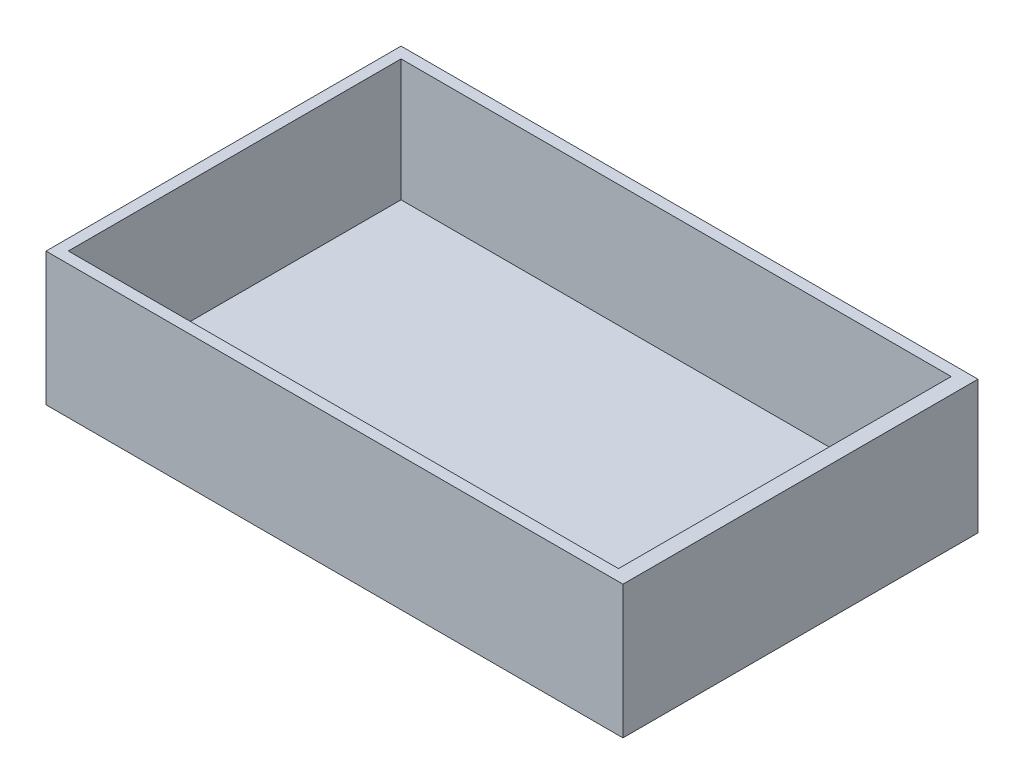
SolidWorks part; units mm, degrees
material "Teak"
ref_plane "Ebene vorne" through (0, 0, 0) normal (0, 0, 1) x (1, 0, 0)
ref_plane "Ebene oben" through (0, 0, 0) normal (0, 1, 0) x (1, 0, 0)
ref_plane "Ebene rechts" through (0, 0, 0) normal (1, 0, 0) x (0, 0, -1)
sketch "Skizze1" plane through (0, 0, 0) normal (0, 1, 0) x (1, 0, 0)
  line L1 (0, 0) -> (520, 0)
  line L2 (0, 0) -> (0, 320)
  line L3 (0, 320) -> (520, 320)
  line L4 (520, 0) -> (520, 320)
  dimension "D1" = 520
  dimension "D2" = 320
extrude "Aufsatz-Linear austragen1" add sketch "Skizze1" along normal blind 10
sketch "Skizze2" plane through (0, 10, 0) normal (0, 1, 0) x (1, 0, 0)
  line L0 (0, 0) -> (0, 320)
  line L1 (0, 320) -> (520, 320)
  line L2 (520, 320) -> (520, 0)
  line L3 (520, 0) -> (0, 0)
  line L5 (10, 10.1318) -> (505.8433, 10.1318)
  line L6 (10, 10.1318) -> (10, 310)
  line L7 (10, 310) -> (505.8433, 310)
  line L8 (505.8433, 10.1318) -> (505.8433, 310)
  dimension "D1" = 10
  dimension "D2" = 10
extrude "Aufsatz-Linear austragen2" add sketch "Skizze2" along normal blind 110
